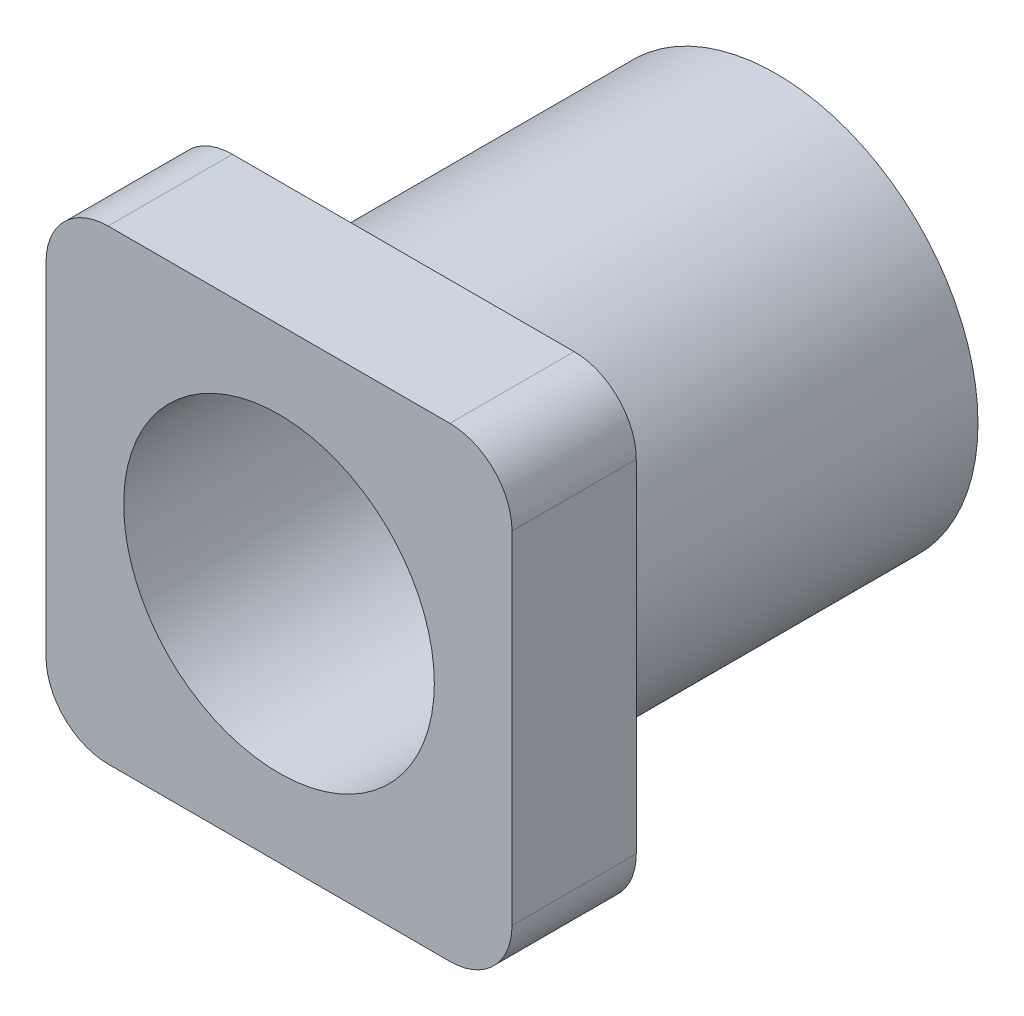
SolidWorks part; units mm, degrees
ref_plane "Front Plane" through (0, 0, 0) normal (0, 0, 1) x (1, 0, 0)
ref_plane "Top Plane" through (0, 0, 0) normal (0, 1, 0) x (1, 0, 0)
ref_plane "Right Plane" through (0, 0, 0) normal (1, 0, 0) x (0, 0, -1)
sketch "Sketch1" plane through (0, 0, 0) normal (0, 0, 1) x (1, 0, 0)
  line L1 (-9.525, -9.525) -> (9.525, -9.525)
  line L2 (-9.525, -9.525) -> (-9.525, 9.525)
  line L3 (-9.525, 9.525) -> (9.525, 9.525)
  line L4 (9.525, -9.525) -> (9.525, 9.525)
  line L5 (-9.525, -9.525) -> (9.525, 9.525) construction
  line L6 (-9.525, 9.525) -> (9.525, -9.525) construction
  point P0 (0, 0)
  dimension "D1" = 19.05
extrude "Boss-Extrude1" add sketch "Sketch1" against normal blind 5.08
sketch "Sketch2" plane through (0, 0, -5.08) normal (0, 0, -1) x (-1, 0, 0)
  circle A0 centre (0, 0) radius 8.255
  dimension "D1" = 16.51
extrude "Boss-Extrude2" add sketch "Sketch2" along normal blind 15.24
sketch "Sketch3" plane through (0, 0, 0) normal (0, 0, 1) x (1, 0, 0)
  line L0 (0, 0) -> (0, 9.525) construction
  line L7 (9.525, 9.525) -> (-9.525, 9.525) construction
  circle A0 centre (0, 0) radius 6.35
  dimension "D1" = 12.7
extrude "Cut-Extrude1" cut sketch "Sketch3" against normal through all
fillet "Fillet1" radius 2.54 4 edges at (9.525, -9.525, -2.54) (-9.525, -9.525, -2.54) (9.525, 9.525, -2.54) (-9.525, 9.525, -2.54)
